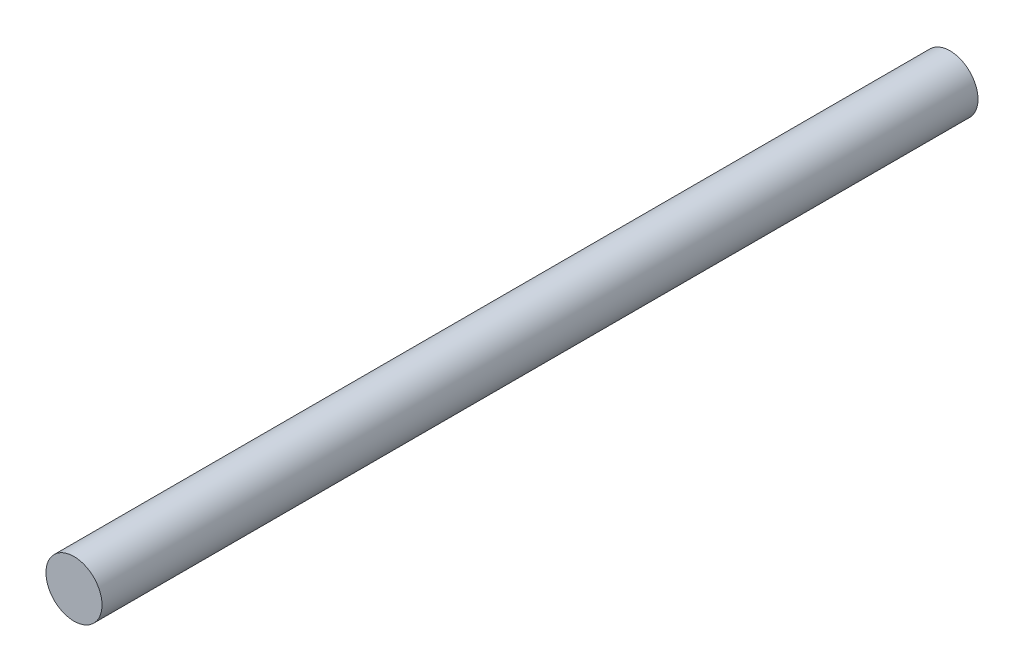
SolidWorks part; units mm, degrees
ref_plane "前基準面" through (0, 0, 0) normal (0, 0, 1) x (1, 0, 0)
ref_plane "上基準面" through (0, 0, 0) normal (0, 1, 0) x (1, 0, 0)
ref_plane "右基準面" through (0, 0, 0) normal (1, 0, 0) x (0, 0, -1)
sketch "草圖1" plane through (0, 0, 0) normal (0, 0, 1) x (1, 0, 0)
  circle A0 centre (0, 0) radius 1.6
  dimension "D1" = 3.2
extrude "填料-伸長1" add sketch "草圖1" along normal blind 50
